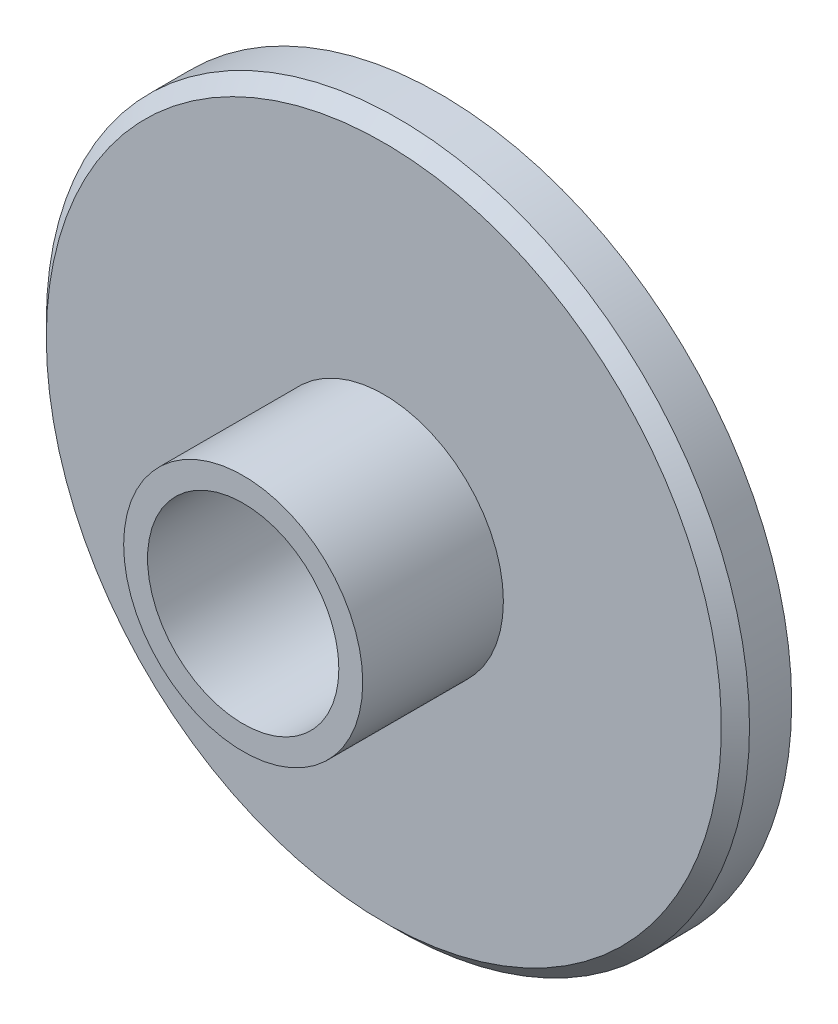
SolidWorks part; units mm, degrees
ref_plane "Front Plane" through (0, 0, 0) normal (0, 0, 1) x (1, 0, 0)
ref_plane "Top Plane" through (0, 0, 0) normal (0, 1, 0) x (1, 0, 0)
ref_plane "Right Plane" through (0, 0, 0) normal (1, 0, 0) x (0, 0, -1)
sketch "Sketch1" plane through (0, 0, 0) normal (1, 0, 0) x (0, 0, -1)
  line L0 (0, 0) -> (9.5, 0) construction
  line L1 (0, 3.4) -> (0, 4.25)
  line L2 (0, 4.25) -> (5, 4.25)
  line L3 (5, 4.25) -> (5, 12.5)
  line L4 (5, 12.5) -> (7, 12.5)
  line L5 (7, 12.5) -> (7, 10.6)
  line L6 (7, 10.6) -> (6, 10.6)
  line L7 (6, 10.6) -> (6, 7.9)
  line L8 (6, 7.9) -> (7, 7.9)
  line L9 (7, 7.9) -> (7, 4.75)
  line L10 (7, 4.75) -> (8.2, 4.75)
  line L11 (8.2, 4.75) -> (8.2, 4)
  line L12 (8.2, 4) -> (8.5, 4)
  line L13 (8.5, 4) -> (8.5, 3.1)
  line L14 (0, 3.4) -> (5.2, 3.4)
  line L15 (5.2, 3.4) -> (5.2, 3.1)
  line L16 (5.2, 3.1) -> (8.5, 3.1)
  dimension "D1" = 6.8
  dimension "D2" = 6.2
  dimension "D3" = 8.5
  dimension "D4" = 25
  dimension "D5" = 9.5
  dimension "D6" = 8
  dimension "D7" = 5
  dimension "D8" = 2
  dimension "D9" = 15.8
  dimension "D10" = 21.2
  dimension "D11" = 1
  dimension "D12" = 8.5
  dimension "D13" = 0.3
  dimension "D14" = 5.2
revolve "Revolve1" add sketch "Sketch1" angle 360 about L0
chamfer "Chamfer1" distance 0.5 angle 45 1 edges at (12.5, 0, -5)
